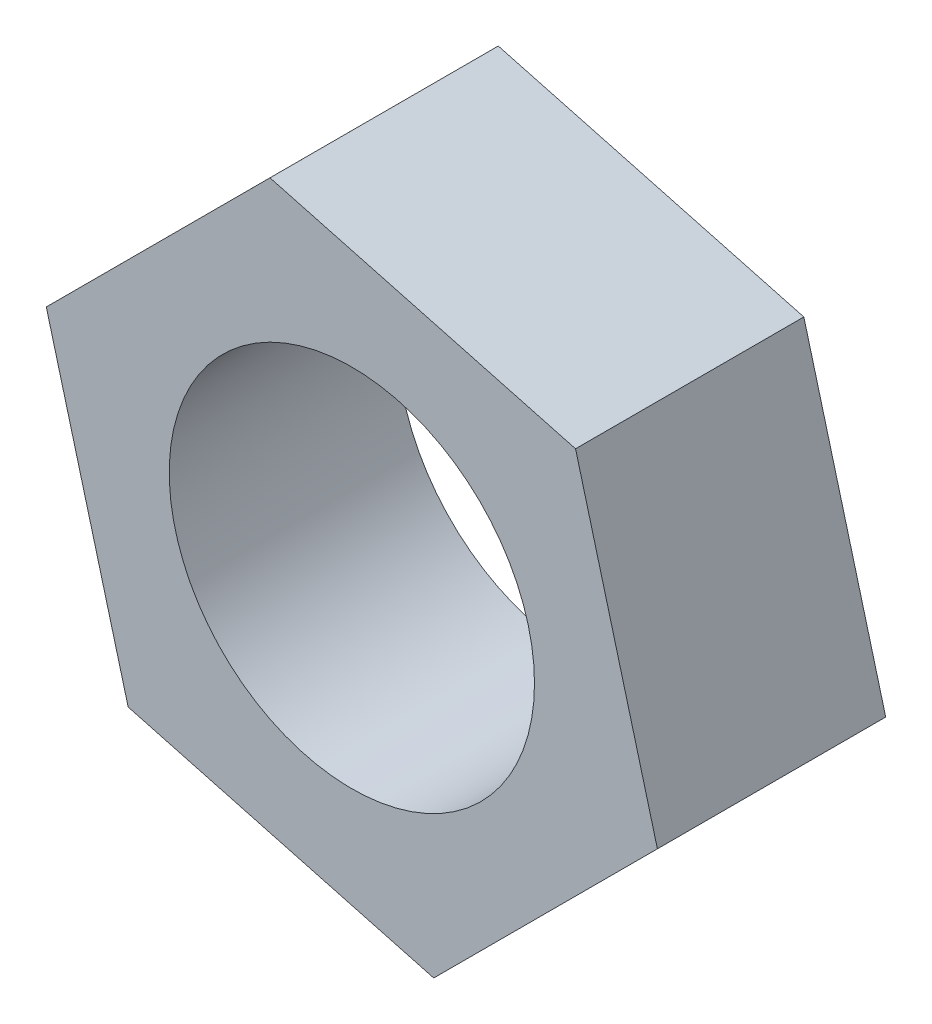
SolidWorks part; units mm, degrees
ref_plane "Alzado" through (0, 0, 0) normal (0, 0, 1) x (1, 0, 0)
ref_plane "Planta" through (0, 0, 0) normal (0, 1, 0) x (1, 0, 0)
ref_plane "Vista lateral" through (0, 0, 0) normal (1, 0, 0) x (0, 0, -1)
sketch "Croquis1" plane through (0, 0, 0) normal (0, 0, 1) x (1, 0, 0)
  circle A0 centre (0, 0) radius 2.5
  circle A1 centre (0, 0) radius 6
extrude "Saliente-Extruir1" add sketch "Croquis1" along normal blind 5
sketch "Croquis2" plane through (0, 0, 5) normal (0, 0, 1) x (1, 0, 0)
  line L8 (-6.6921, 1.7932) -> (-1.7931, 6.6921)
  line L9 (-1.7931, 6.6921) -> (4.899, 4.8989)
  line L10 (4.899, 4.8989) -> (6.6921, -1.7932)
  line L11 (6.6921, -1.7932) -> (1.7931, -6.6921)
  line L12 (1.7931, -6.6921) -> (-4.899, -4.8989)
  line L13 (-4.899, -4.8989) -> (-6.6921, 1.7932)
  circle A3 centre (0, 0) radius 4
  point P13 (0, 0)
  point P15 (-4.2426, 4.2426)
  point P28 (0, 0)
  dimension "D1" = 8
  dimension "D2" = 6
extrude "Saliente-Extruir2" add sketch "Croquis2" against normal blind 5
sketch "Croquis3" plane through (0, 0, 5) normal (0, 0, 1) x (1, 0, 0)
  circle A0 centre (0, 0) radius 4
extrude "Cortar-Extruir1" cut sketch "Croquis3" against normal blind 10
